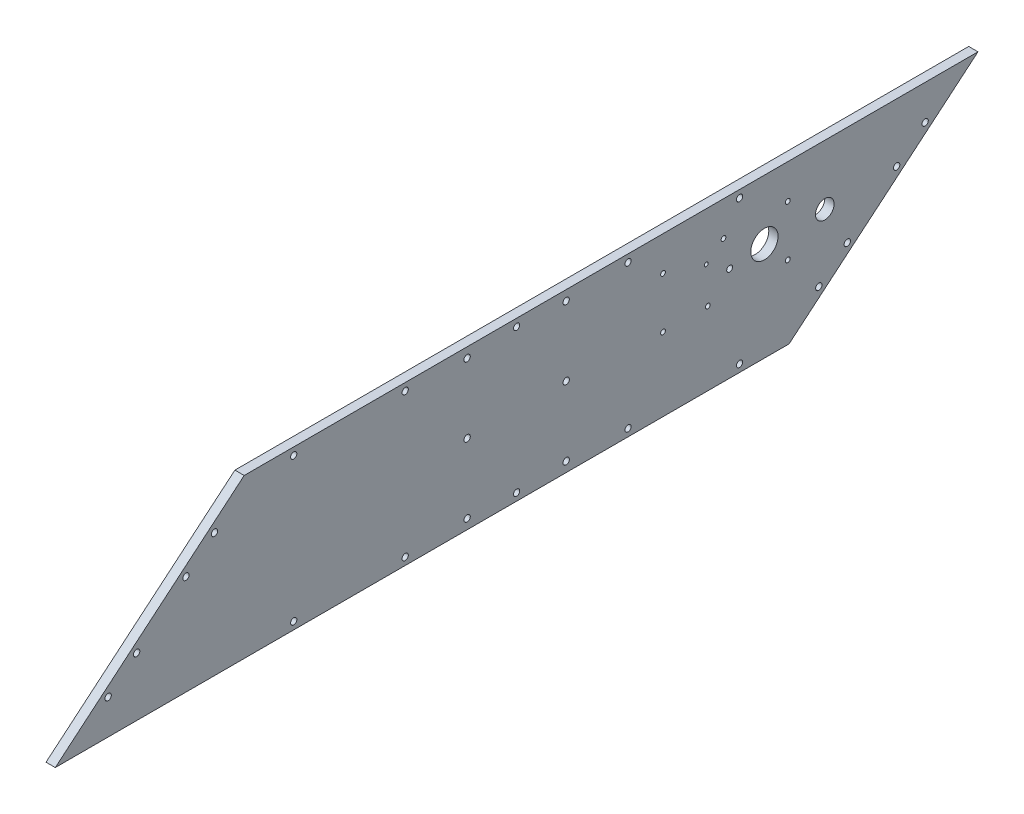
SolidWorks part; units mm, degrees
material "6061-T6 (SS)"
ref_plane "Front Plane" through (0, 0, 0) normal (0, 0, 1) x (1, 0, 0)
ref_plane "Top Plane" through (0, 0, 0) normal (0, 1, 0) x (1, 0, 0)
ref_plane "Right Plane" through (0, 0, 0) normal (1, 0, 0) x (0, 0, -1)
sketch "Sketch1" plane through (0, 0, 0) normal (1, 0, 0) x (0, 0, -1)
  line L0 (0, 12.7) -> (0, -12.7) construction
  line L1 (0, -12.7) -> (33.2976, -40.64) construction
  line L2 (33.2976, -40.64) -> (312.6976, -40.64)
  line L3 (312.6976, -40.64) -> (345.9952, -12.7)
  line L4 (345.9952, -12.7) -> (345.9952, 12.7) construction
  line L5 (345.9952, 12.7) -> (312.6976, 40.64) construction
  line L6 (312.6976, 40.64) -> (33.2976, 40.64)
  line L7 (33.2976, 40.64) -> (0, 12.7)
  line L8 (33.2976, 40.64) -> (33.2976, -40.64) construction
  line L9 (312.6976, 40.64) -> (312.6976, -40.64) construction
  line L10 (0, 0) -> (345.9952, 0) construction
  line L11 (0, 12.7) -> (-63.5681, -40.64)
  line L12 (-63.5681, -40.64) -> (33.2976, -40.64)
  line L13 (312.6976, 40.64) -> (409.5633, 40.64)
  line L14 (409.5633, 40.64) -> (345.9952, -12.7)
  point P10 (33.2976, 0)
  point P12 (312.6976, 0)
  dimension "D1" = 81.28
  dimension "D2" = 279.4
  dimension "D3" = 25.4
  dimension "D4" = 40
extrude "Boss-Extrude1" add sketch "Sketch1" along normal blind 4.7625
sketch "Sketch2" plane through (4.7625, 0, 0) normal (1, 0, 0) x (0, 0, -1)
  line L0 (-3.2177, 10) -> (373.048, 10) construction
  line L1 (312.6976, -40.64) -> (409.5633, 40.64) construction
  line L2 (345.048, 10) -> (245.048, 10) construction
  line L3 (245.048, -5) -> (345.048, -5) construction
  line L4 (245.048, -5) -> (245.048, 25) construction
  line L5 (245.048, 25) -> (345.048, 25) construction
  line L6 (345.048, -5) -> (345.048, 25) construction
  line L7 (0, 0) -> (361.1305, 0) construction
  line L9 (33.2976, 40.64) -> (-63.5681, -40.64) construction
  circle A0 centre (300.048, 10) radius 6.9977
  circle A1 centre (282.2147, 8) radius 1.4986
  circle A2 centre (270.2178, 15.9334) radius 0.9906
  circle A3 centre (282.2147, 8) radius 11.4777 construction
  circle A4 centre (270.2178, 15.9334) radius 7.1501 construction
  circle A5 centre (300.048, 10) radius 12.827 construction
  circle A6 centre (261.048, 10) radius 14 construction
  circle A7 centre (282.2147, 8) radius 5.1181 construction
  circle A8 centre (331.0042, 10) radius 4.7625
  point P11 (300.048, 10)
  point P12 (282.2147, 8)
  point P13 (270.2178, 15.9334)
  point P23 (261.048, 10)
  dimension "D5" = 13.9954
  dimension "D6" = 2.9972
  dimension "D7" = 1.9812
  dimension "D8" = 25.654
  dimension "D9" = 22.9553
  dimension "D10" = 14.3002
  dimension "D12" = 28
  dimension "D13" = 10.2362
  dimension "D17" = 9.525
  dimension "D1" = 17.9451
  dimension "D2" = 14.3828
  dimension "D3" = 30
  dimension "D4" = 100
  dimension "D11" = 10.922
  dimension "D14" = 16
  dimension "D15" = 13
  dimension "D16" = 55
  dimension "D18" = 30.9562
  dimension "D19" = 28
  dimension "D20" = 10
extrude "Gearbox (with Press fits)" cut sketch "Sketch2" against normal through all
sketch "Sketch6" plane through (4.7625, 0, 0) normal (1, 0, 0) x (0, 0, -1)
  line L0 (0, 0) -> (361.1305, 0) construction
  line L2 (28.757, 36.83) -> (405.0227, 36.83) construction
  line L3 (33.2976, 40.64) -> (-63.5681, -40.64) construction
  line L5 (409.5633, 40.64) -> (33.2976, 40.64) construction
  line L6 (312.6976, -40.64) -> (409.5633, 40.64) construction
  circle A0 centre (287.2976, 36.83) radius 1.5939
  circle A1 centre (230.1476, 36.83) radius 1.5939
  circle A2 centre (172.9976, 36.83) radius 1.5939
  circle A3 centre (115.8476, 36.83) radius 1.5938
  circle A4 centre (58.6976, 36.83) radius 1.5938
  circle A5 centre (58.6976, -36.83) radius 1.5938
  circle A6 centre (115.8476, -36.83) radius 1.5938
  circle A7 centre (172.9976, -36.83) radius 1.5939
  circle A8 centre (230.1476, -36.83) radius 1.5939
  circle A9 centre (287.2976, -36.83) radius 1.5939
  dimension "D2" = 3.1877
  dimension "D1" = 3.81
  dimension "D3" = 25.4
  dimension "D4" = 5
extrude "Cut-Extrude2" cut sketch "Sketch6" against normal through all
hole_wizard "#4 Clearance Hole2" positions "Sketch8" profile "Sketch7" hole size "#4" standard "ANSI Inch" end condition through all
sketch "Sketch8" plane through (4.7625, 0, 0) normal (1, 0, 0) x (0, 0, -1)
  line L0 (0, 0) -> (361.1305, 0) construction
  line L1 (312.6976, -40.64) -> (409.5633, 40.64) construction
  line L3 (27.2435, 35.56) -> (403.5092, 35.56) construction
  line L4 (33.2976, 40.64) -> (-63.5681, -40.64) construction
  line L5 (147.5976, 35.56) -> (147.5976, -35.56) construction
  line L7 (198.3976, 35.56) -> (198.3976, -35.56) construction
  line L8 (409.5633, 40.64) -> (33.2976, 40.64) construction
  point P13 (147.5976, 35.56)
  point P15 (198.3976, 35.56)
  point P18 (198.3976, -35.56)
  point P19 (147.5976, -35.56)
  point P28 (147.5976, 0)
  point P30 (198.3976, 0)
  dimension "D1" = 114.3
  dimension "D2" = 165.1
  dimension "D3" = 5.08
sketch "Sketch7" plane through (4.7625, 35.56, -147.5976) normal (0, 1, 0) x (0, 0, -1)
  line L0 (0, 0) -> (0, 4.7625)
  line L1 (0, 4.7625) -> (1.6319, 4.7625)
  line L2 (1.6319, 4.7625) -> (1.6319, 0)
  line L5 (1.6319, 0) -> (0, 0)
  line L11 (0, -6.35) -> (0, 107.95) construction
  dimension "Thru Hole Dia." = 3.2639
  dimension "Thru Hole Depth" = 4.7625
hole_wizard "#2 Clearance Hole1" positions "Sketch10" profile "Sketch9" hole size "#2" standard "ANSI Inch"
sketch "Sketch10" plane through (4.7625, 0, 0) normal (1, 0, 0) x (0, 0, -1)
  line L0 (245.048, 40.64) -> (245.048, -40.64) construction
  line L1 (409.5633, 40.64) -> (33.2976, 40.64) construction
  line L2 (-63.5681, -40.64) -> (312.6976, -40.64) construction
  line L4 (248.048, 40.64) -> (248.048, -40.64) construction
  line L6 (245.048, 23) -> (312.2578, 23) construction
  line L8 (245.048, -6) -> (328.5196, -6) construction
  line L10 (245.048, -3) -> (332.5851, -3) construction
  line L11 (312.048, 23) -> (312.048, -3) construction
  line L12 (373.048, 10) -> (261.048, 10) construction
  line L13 (312.6976, -40.64) -> (409.5633, 40.64) construction
  line L14 (331.0042, 10) -> (331.0042, 40.64) construction
  circle A0 centre (331.0042, 10) radius 4.7625 construction
  point P25 (248.048, -3)
  point P27 (248.048, 23)
  point P29 (271.048, -3)
  point P31 (312.048, -3)
  point P33 (279.048, 23)
  point P35 (312.048, 23)
  dimension "D1" = 3
  dimension "D2" = 3
  dimension "D3" = 26
  dimension "D4" = 34
  dimension "D5" = 67
  dimension "D6" = 29
  dimension "D7" = 69.9562
  dimension "D8" = 16
  dimension "D9" = 16
sketch "Sketch9" plane through (4.7625, -3, -248.048) normal (0, 1, 0) x (0, 0, -1)
  line L0 (0, 0) -> (0, 5.5586)
  line L1 (0, 5.5586) -> (1.2192, 4.826)
  line L2 (1.2192, 4.826) -> (1.2192, 0)
  line L5 (1.2192, 0) -> (0, 0)
  line L10 (0, 5.5586) -> (-1.2192, 4.826) construction
  line L11 (0, -6.35) -> (0, 107.95) construction
  dimension "Hole Dia." = 2.4384
  dimension "Hole Depth" = 4.826
  dimension "Drill Angle" = 118
hole_wizard "#4 Clearance Hole1" positions "Sketch12" profile "Sketch11" hole size "#4" standard "ANSI Inch"
sketch "Sketch12" plane through (4.7625, 0, 0) normal (1, 0, 0) x (0, 0, -1)
  line L9 (-15.1353, 0) -> (361.1305, 0) construction
  line L10 (33.2976, 40.64) -> (-63.5681, -40.64) construction
  line L11 (312.6976, -40.64) -> (409.5633, 40.64) construction
  line L13 (403.636, 40.64) -> (306.7703, -40.64) construction
  line L14 (409.5633, 40.64) -> (33.2976, 40.64) construction
  line L15 (-63.5681, -40.64) -> (312.6976, -40.64) construction
  line L17 (39.2249, 40.64) -> (-57.6408, -40.64) construction
  line L18 (355.2032, 0) -> (-9.208, 0) construction
  line L19 (-36.4485, -22.8575) -> (327.9626, -22.8575) construction
  line L21 (-21.8554, -10.6124) -> (342.5558, -10.6124) construction
  line L23 (3.4394, 10.6124) -> (367.8505, 10.6124) construction
  line L25 (18.0326, 22.8575) -> (382.4437, 22.8575) construction
  point P40 (327.9626, -22.8575)
  point P42 (342.5558, -10.6124)
  point P44 (367.8505, 10.6124)
  point P46 (382.4437, 22.8575)
  point P54 (-36.4485, -22.8575)
  point P56 (-21.8554, -10.6124)
  point P58 (3.4394, 10.6124)
  point P60 (18.0326, 22.8575)
  dimension "D1" = 16.51
  dimension "D2" = 19.05
  dimension "D3" = 16.51
  dimension "D4" = 19.05
  dimension "D5" = 3.81
  dimension "D6" = 3.81
sketch "Sketch11" plane through (4.7625, -22.8575, -327.9626) normal (0, 1, 0) x (0, 0, -1)
  line L0 (0, 0) -> (0, 5.8066)
  line L1 (0, 5.8066) -> (1.6319, 4.826)
  line L2 (1.6319, 4.826) -> (1.6319, 0)
  line L5 (1.6319, 0) -> (0, 0)
  line L10 (0, 5.8066) -> (-1.6319, 4.826) construction
  line L11 (0, -6.35) -> (0, 107.95) construction
  dimension "Hole Dia." = 3.2639
  dimension "Hole Depth" = 4.826
  dimension "Drill Angle" = 118
